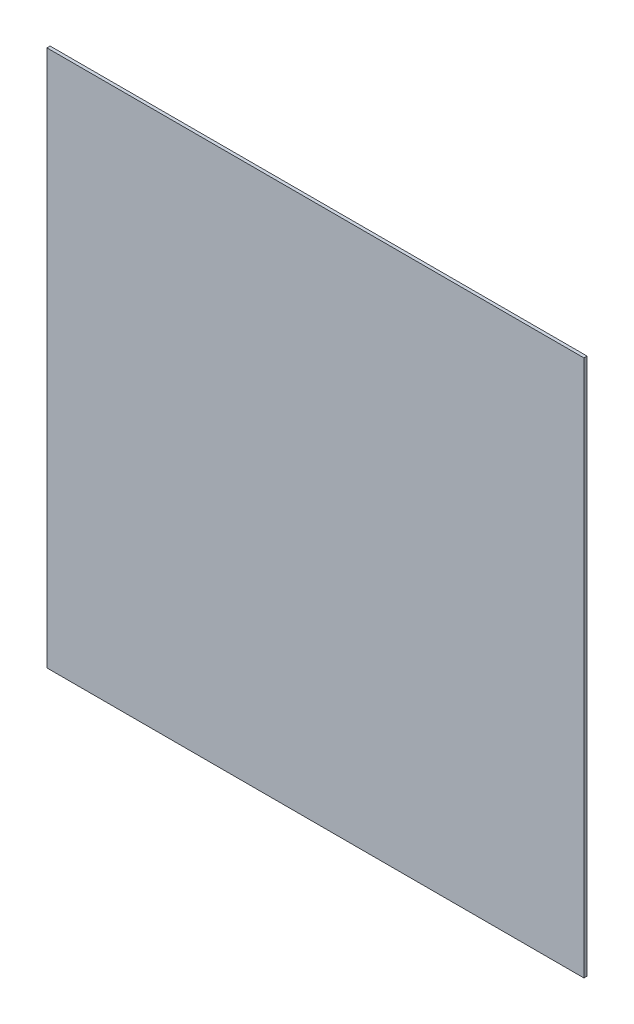
SolidWorks part; units mm, degrees
ref_plane "Front Plane" through (0, 0, 0) normal (0, 0, 1) x (1, 0, 0)
ref_plane "Top Plane" through (0, 0, 0) normal (0, 1, 0) x (1, 0, 0)
ref_plane "Right Plane" through (0, 0, 0) normal (1, 0, 0) x (0, 0, -1)
sketch "Sketch1" plane through (0, 0, 0) normal (0, 0, 1) x (1, 0, 0)
  line L1 (255, -255) -> (-255, -255)
  line L2 (255, -255) -> (255, 255)
  line L3 (255, 255) -> (-255, 255)
  line L4 (-255, -255) -> (-255, 255)
  line L5 (255, -255) -> (-255, 255) construction
  line L6 (255, 255) -> (-255, -255) construction
  point P0 (0, 0)
  dimension "D1" = 510
  dimension "D2" = 510
extrude "Boss-Extrude1" add sketch "Sketch1" along normal blind 3
